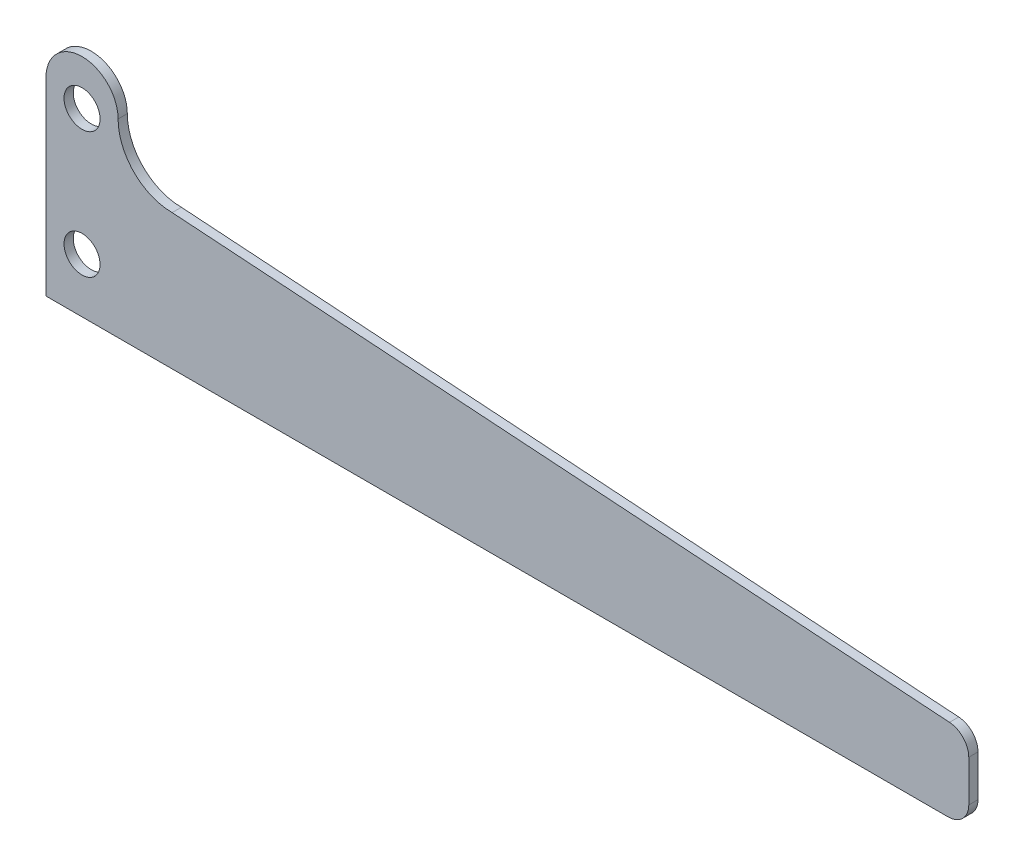
SolidWorks part; units mm, degrees
ref_plane "Front Plane" through (0, 0, 0) normal (0, 0, 1) x (1, 0, 0)
ref_plane "Top Plane" through (0, 0, 0) normal (0, 1, 0) x (1, 0, 0)
ref_plane "Right Plane" through (0, 0, 0) normal (1, 0, 0) x (0, 0, -1)
sketch "Sketch1" plane through (0, 0, 0) normal (0, 0, 1) x (1, 0, 0)
  line L0 (3.175, 19.05) -> (3.175, 0) construction
  line L1 (0, 0) -> (6.35, 0) construction
  line L2 (0, 0) -> (0, 19.05)
  line L3 (0, 19.05) -> (6.35, 19.05)
  line L4 (6.35, 0) -> (6.35, 19.05) construction
  line L5 (3.175, 15.0813) -> (3.175, 3.9688) construction
  line L6 (6.35, 0) -> (81.2824, 0) construction
  line L9 (0, 0) -> (0, -0.8128)
  line L10 (0, -0.8128) -> (81.2824, -0.8128)
  line L11 (81.2824, -0.8128) -> (81.2824, 0)
  line L12 (0, 19.05) -> (-1.5875, 19.05) construction
  line L13 (-1.5875, 19.05) -> (-1.5875, -0.8128) construction
  line L14 (-1.5875, -0.8128) -> (0, -0.8128) construction
  line L15 (81.2824, 11.1125) -> (6.35, 11.1125) construction
  line L16 (81.2824, 0) -> (81.2824, 11.1125) construction
  line L17 (11.1125, 11.1125) -> (81.2824, 6.35)
  line L18 (81.2824, 6.35) -> (81.2824, 0)
  line L19 (11.8116, 2.8283) -> (75.8208, 2.8283)
  circle A0 centre (3.175, 15.0813) radius 1.5875
  circle A1 centre (3.175, 3.9688) radius 1.5875
  circle A2 centre (3.175, 15.875) radius 3.175
  circle A3 centre (3.175, 3.175) radius 3.175
  circle A4 centre (11.1125, 15.875) radius 4.7625
  circle A5 centre (79.4619, 4.6488) radius 1.8205
  circle A6 centre (79.4619, 1.0077) radius 1.8205
  circle A7 centre (75.8208, 1.0077) radius 1.8205
  circle A8 centre (8.1705, 1.0077) radius 1.8205
  circle A9 centre (11.8116, 1.0077) radius 1.8205
  point P11 (3.175, 9.525)
  point P12 (3.175, 9.525)
  point P30 (6.35, 15.875)
  point P39 (0, 0)
  point P42 (0, 0)
  dimension "D1" = 19.05
  dimension "D2" = 3.175
  dimension "D8" = 11.1125
  dimension "D9" = 6.35
  dimension "D3" = 6.35
  dimension "D4" = 11.1125
  dimension "D5" = 0.8128
  dimension "D6" = 81.2824
  dimension "D7" = 1.5875
extrude "Boss-Extrude1" add sketch "Sketch1" along normal blind 0.8128
